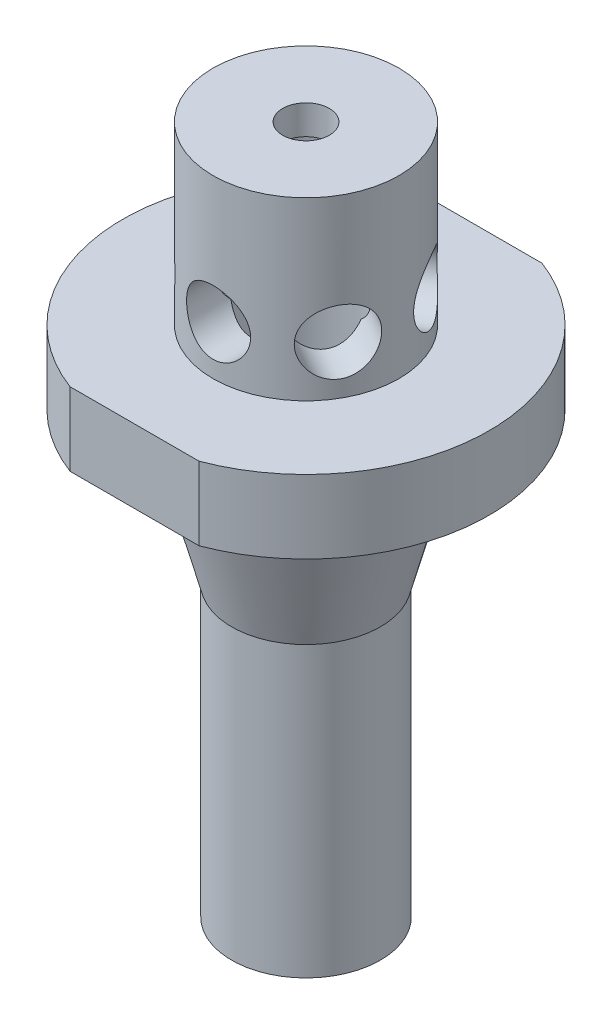
SolidWorks part; units mm, degrees
ref_plane "Front Plane" through (0, 0, 0) normal (0, 0, 1) x (1, 0, 0)
ref_plane "Top Plane" through (0, 0, 0) normal (0, 1, 0) x (1, 0, 0)
ref_plane "Right Plane" through (0, 0, 0) normal (1, 0, 0) x (0, 0, -1)
sketch "Sketch1" plane through (0, 0, 0) normal (1, 0, 0) x (0, 0, -1)
  line L0 (0, 0) -> (0, 97.3762) construction
  line L1 (0, 34) -> (12.7, 34)
  line L2 (12.7, 34) -> (12.7, 10)
  line L3 (12.7, 10) -> (25, 10)
  line L4 (25, 10) -> (25, 0)
  line L5 (25, 0) -> (15.68, 0)
  line L7 (0, 97.3762) -> (0, -129.0791) construction
  line L8 (0, -60) -> (0, 34)
  line L9 (10.16, -60) -> (0, -60)
  line L11 (10.16, 34) -> (10.16, 43.9813) construction
  line L12 (10.16, -60) -> (10.16, -20.6009)
  line L13 (15.68, 0) -> (10.16, -20.6009)
  dimension "D1" = 15
  dimension "D2" = 10.16
  dimension "D3" = 25
  dimension "D4" = 12.7
  dimension "D5" = 10
  dimension "D7" = 24
  dimension "D8" = 60
  dimension "D9" = 15.68
revolve "Revolve1" add sketch "Sketch1" angle 360 about L0
cosmetic thread "Cosmetic Thread1" parameters "D1"=10, "D2"=21.6205
sketch "Sketch5" plane through (0, -60, 0) normal (0, -1, 0) x (1, 0, 0)
  circle A1 centre (0, 0) radius 7.5
  dimension "D1" = 15
extrude "Cut-Extrude1" cut sketch "Sketch5" against normal blind 90
sketch "Sketch6" plane through (0, 0, 0) normal (0, 0, 1) x (1, 0, 0)
  circle A0 centre (0, 16.66) radius 4.3704
extrude "Cut-Extrude2" cut sketch "Sketch6" against normal mid plane 40
pattern_circular "CirPattern1" count 6 over 360 about axis through (0, 34, 0) along (0, -1, 0) of "Cut-Extrude2"
sketch "Sketch8" plane through (0, 10, 0) normal (0, 1, 0) x (1, 0, 0)
  line L0 (-8.863, 23.4) -> (8.863, 23.4)
  line L1 (-25, 0) -> (25, 0) construction
  line L2 (-8.863, -23.4) -> (8.863, -23.4)
  arc A0 (-8.863, -23.4) -> (8.863, -23.4) centre (0, 0) ccw
  arc A1 (8.863, 23.4) -> (-8.863, 23.4) centre (0, 0) ccw
  dimension "D1" = 23.4
  dimension "D2" = 23.4
extrude "Cut-Extrude3" cut sketch "Sketch8" against normal up to next
sketch "Sketch9" plane through (0, 34, 0) normal (0, 1, 0) x (1, 0, 0)
  circle A0 centre (0, 0) radius 12.7
  circle A1 centre (0, 0) radius 25
  dimension "D1" = 25.4
  dimension "D2" = 50
sketch "Sketch10" plane through (0, 0, 0) normal (1, 0, 0) x (0, 0, -1)
  line L0 (0, 34) -> (0, 10) construction
  line L1 (25, 34) -> (-25, 34) construction
  line L2 (23.4, 10) -> (-23.4, 10) construction
  dimension "D1" = 24
sketch "Sketch11" plane through (0, 34, 0) normal (0, 1, 0) x (1, 0, 0)
  circle A0 centre (0, 0) radius 3.18
  dimension "D1" = 6.36
extrude "Cut-Extrude4" cut sketch "Sketch11" against normal through all
cosmetic thread "Cosmetic Thread2" parameters "D2"=7.9375
